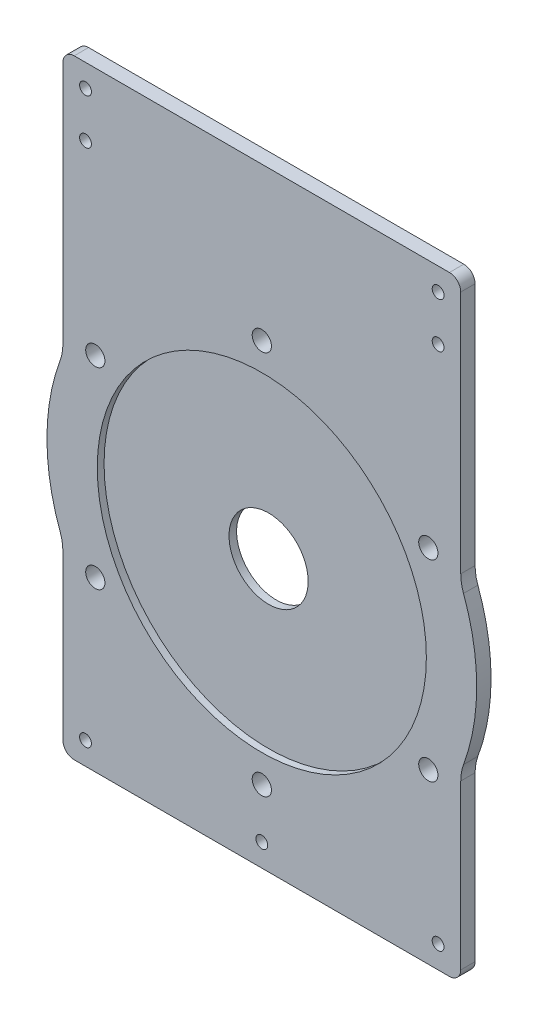
SolidWorks part; units mm, degrees
ref_plane "Front" through (0, 0, 0) normal (0, 0, 1) x (1, 0, 0)
ref_plane "Top" through (0, 0, 0) normal (0, 1, 0) x (1, 0, 0)
ref_plane "Right" through (0, 0, 0) normal (1, 0, 0) x (0, 0, -1)
sketch "Sketch1" plane through (0, 0, 0) normal (0, 0, 1) x (1, 0, 0)
  circle A0 centre (0, 0) radius 95
  dimension "D1" = 190
extrude "Boss-Extrude1" add sketch "Sketch1" along normal blind 6.35
sketch "Sketch2" plane through (0, 0, 6.35) normal (0, 0, 1) x (1, 0, 0)
  line L0 (0, 0) -> (0, -117) construction
  line L1 (-127.946, -77) -> (-87.946, -77) construction
  line L2 (-127.946, -77) -> (-127.946, -117) construction
  line L3 (-127.946, -117) -> (-87.946, -117) construction
  line L4 (-87.946, -77) -> (-87.946, -117) construction
  line L5 (-127.946, -77) -> (-87.946, -117) construction
  line L6 (-127.946, -117) -> (-87.946, -77) construction
  line L7 (87.946, -117) -> (-87.946, -117)
  line L8 (-87.946, -117) -> (-87.946, -35.9235)
  line L9 (0, 0) -> (-95, 0) construction
  line L10 (87.946, -117) -> (87.946, -35.9235)
  circle A0 centre (0, 0) radius 95 construction
  arc A1 (-87.946, -35.9235) -> (87.946, -35.9235) centre (0, 0) ccw
  point P4 (-107.946, -97)
  dimension "D3" = 87.946
  dimension "D4" = 77
  dimension "D1" = 40
  dimension "D2" = 40
extrude "Boss-Extrude2" add sketch "Sketch2" against normal up to surface (6.35 mm away) up to face at (95, 0, 0)
sketch "Sketch3" plane through (0, 0, 6.35) normal (0, 0, 1) x (1, 0, 0)
  line L0 (-87.946, -117) -> (87.946, -117) construction
  line L1 (-87.946, -35.9235) -> (-87.946, -117) construction
  line L2 (0, 0) -> (0, -117) construction
  line L3 (77.946, -107) -> (-77.946, -107) construction
  circle A0 centre (-77.946, -107) radius 2.6162
  circle A3 centre (77.946, -107) radius 2.6162
  circle A4 centre (0, -107) radius 2.6162
  dimension "D1" = 5.2324
  dimension "D2" = 10
  dimension "D3" = 10
sketch "Sketch4" plane through (0, 0, 6.35) normal (0, 0, 1) x (1, 0, 0)
  circle A0 centre (0, 0) radius 72.75
  dimension "D1" = 145.5
extrude "Cut-Extrude2" cut sketch "Sketch4" against normal blind 3
sketch "Sketch5" plane through (0, 0, 3.35) normal (0, 0, 1) x (1, 0, 0)
  circle A0 centre (0, 0) radius 17.5
  dimension "D1" = 35
extrude "Cut-Extrude3" cut sketch "Sketch5" against normal up to next
sketch "Sketch6" plane through (0, 0, 6.35) normal (0, 0, 1) x (1, 0, 0)
  line L0 (0, 0) -> (0, 85) construction
  circle A0 centre (0, 85) radius 3.75
  circle A1 centre (73.6122, 42.5) radius 3.75
  circle A2 centre (73.6122, -42.5) radius 3.75
  circle A3 centre (0, -85) radius 3.75
  circle A4 centre (-73.6122, -42.5) radius 3.75
  circle A5 centre (-73.6122, 42.5) radius 3.75
  point P16 (0, 0)
  dimension "D2" = 7.5
  dimension "D1" = 85
  dimension "D3" = 6
hole_wizard "Tap Drill for M10x1.5 Tap1" positions "3DSketch1" profile "Sketch7" hole size "M10x1.5" standard "ANSI Metric" end condition up to next
sketch3d "3DSketch1"
  point P0 (0, 85, 6.35)
  point P3 (73.6122, 42.5, 6.35)
  point P6 (73.6122, -42.5, 6.35)
  point P9 (0, -85, 6.35)
  point P12 (-73.6122, -42.5, 6.35)
  point P15 (-73.6122, 42.5, 6.35)
sketch "Sketch7" plane through (0, 85, 6.35) normal (1, 0, 0) x (0, -1, 0)
  line L0 (0, 0) -> (0, 6.35)
  line L1 (0, 6.35) -> (4.25, 6.35)
  line L2 (4.25, 6.35) -> (4.25, 0)
  line L5 (4.25, 0) -> (0, 0)
  line L11 (0, -6.35) -> (0, 107.95) construction
  dimension "Thru Hole Dia." = 8.5
  dimension "Thru Hole Depth" = 6.35
extrude "Cut-Extrude4" cut sketch "Sketch3" against normal up to next
sketch "Sketch8" plane through (0, 0, 6.35) normal (0, 0, 1) x (1, 0, 0)
  line L1 (-66.946, 152.5499) -> (66.946, 152.5499) construction
  line L4 (-87.946, 92.5499) -> (-87.946, 152.5499) construction
  line L5 (87.946, 152.5499) -> (87.946, 92.5499) construction
  line L6 (87.946, 152.5499) -> (-87.946, 152.5499)
  line L7 (-87.946, 152.5499) -> (-87.946, 35.9235)
  line L8 (87.946, 152.5499) -> (87.946, 35.9235)
  arc A0 (87.946, -35.9235) -> (-87.946, -35.9235) centre (0, 0) ccw construction
  arc A1 (87.946, 35.9235) -> (-87.946, 35.9235) centre (0, 0) ccw
extrude "Boss-Extrude3" add sketch "Sketch8" against normal up to surface (6.35 mm away) up to face at (-75.3298, -107, 0)
sketch "Sketch9" plane through (0, 0, 6.35) normal (0, 0, 1) x (1, 0, 0)
  line L0 (87.946, 152.5499) -> (-87.946, 152.5499) construction
  line L1 (-87.946, 152.5499) -> (-87.946, 35.9235) construction
  line L2 (-77.946, 142.5499) -> (-77.946, 122.5499) construction
  line L3 (0, 152.5499) -> (0, 0) construction
  circle A0 centre (-77.946, 142.5499) radius 2.6162
  circle A1 centre (-77.946, 122.5499) radius 2.6162
  circle A2 centre (-77.946, -107) radius 2.6162 construction
  circle A3 centre (77.946, 122.5499) radius 2.6162
  circle A4 centre (77.946, 142.5499) radius 2.6162
  dimension "D1" = 20
  dimension "D2" = 10
  dimension "D3" = 10
extrude "Cut-Extrude5" cut sketch "Sketch9" against normal up to next
fillet "Fillet1" radius 20 4 edges at (-87.946, 35.9235, 3.175) (-87.946, -35.9235, 3.175) (87.946, -35.9235, 3.175) (87.946, 35.9235, 3.175)
fillet "Fillet2" radius 5 4 edges at (-87.946, -117, 3.175) (87.946, -117, 3.175) (87.946, 152.5499, 3.175) (-87.946, 152.5499, 3.175)
